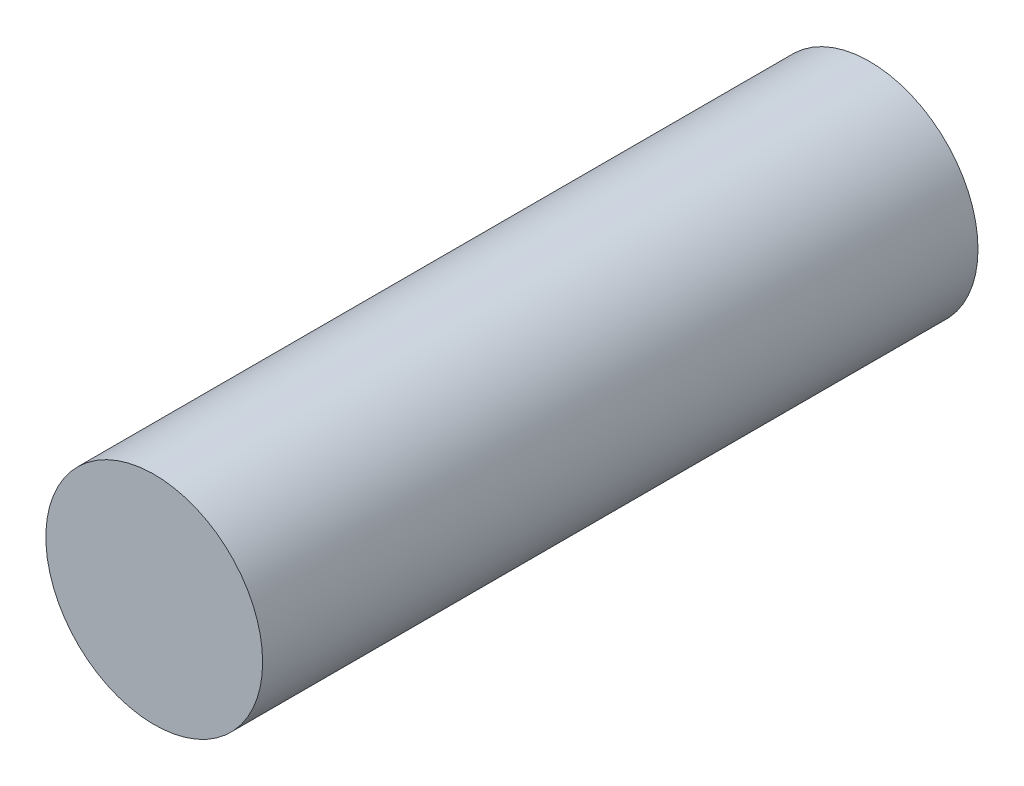
SolidWorks part; units mm, degrees
ref_plane "Front Plane" through (0, 0, 0) normal (0, 0, 1) x (1, 0, 0)
ref_plane "Top Plane" through (0, 0, 0) normal (0, 1, 0) x (1, 0, 0)
ref_plane "Right Plane" through (0, 0, 0) normal (1, 0, 0) x (0, 0, -1)
sketch "Sketch1" plane through (0, 0, 0) normal (0, 0, 1) x (1, 0, 0)
  circle A0 centre (0, 0) radius 6.35
extrude "Boss-Extrude2" add sketch "Sketch1" along normal blind 41.91 contours A0
